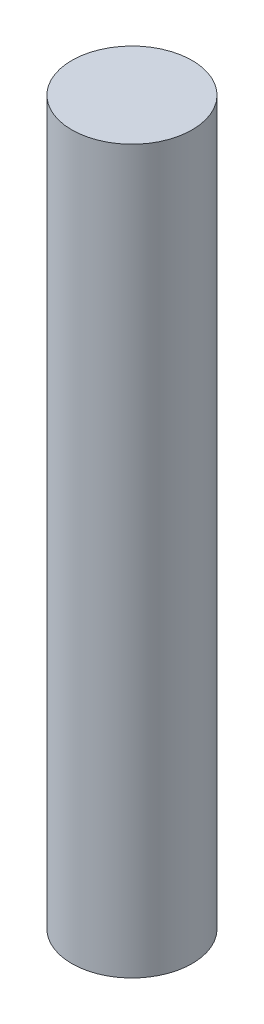
SolidWorks part; units mm, degrees
material "AISI 1020"
ref_plane "Front Plane" through (0, 0, 0) normal (0, 0, 1) x (1, 0, 0)
ref_plane "Top Plane" through (0, 0, 0) normal (0, 1, 0) x (1, 0, 0)
ref_plane "Right Plane" through (0, 0, 0) normal (1, 0, 0) x (0, 0, -1)
sketch "Sketch1" plane through (0, 0, 0) normal (0, 1, 0) x (1, 0, 0)
  circle A0 centre (0, 0) radius 1
  dimension "D1" = 2
extrude "Boss-Extrude1" add sketch "Sketch1" along normal blind 12
equation "\"D1@Sketch1\"=\"impeller dowel diameter\""
equation "\"D1@Boss-Extrude1\"=\"impeller dowel length\" "
equation "\"bearing OD\"= 30mm"
equation "\"bearing outer race thickness\"= 1mm"
equation "\"bearing ID\"= 10mm"
equation "\"bearing depth\"= 9mm"
equation "\"bearing inner race thickness\"= 1mm"
equation "\"small seal OD\"= 20mm"
equation "\"small seal ID\"= 8mm"
equation "\"small seal depth\"= 6mm"
equation "\"big seal OD\"= 30mm"
equation "\"big seal ID\"= 15mm"
equation "\"big seal depth\"= 8mm"
equation "\"z\"= 6"
equation "\"de\"= .4in"
equation "\"d2\"= 1.4in"
equation "\"d_exit\"=\"b2\""
equation "\"theta\"= 15"
equation "\"b2\"= .1117in"
equation "\"b1\"= \"b2\" + (\"d2\"/2 - \"de\"/2)*sin(\"theta\")"
equation "\"s\"= ( 1/\"z\")*(3.14*\"de\" - (3.14*(\"de\"^2) / (4*(\"b1\"))))"
equation "\"s_opening\"= (3.14*\"de\" - \"z\"*\"s\")/\"z\""
equation "\"area_eye\"=3.14*(\"de\"^2)/4"
equation "\"single_channel_area\"=\"s_opening\"*\"b1\""
equation "\"impeller upper clearance\"= .5mm"
equation "\"impeller horizontal clearance\"= .5mm"
equation "\"impeller bottom clearance\"= .5mm"
equation "\"impeller base thickness\"= 2mm"
equation "\"impeller boss depth\"= 14mm"
equation "\"impeller dowel diameter\"= 2mm"
equation "\"impeller bolt head diameter\"= 7.5mm"
equation "\"impeller bolt head depth\"= 4mm"
equation "\"impeller boss diameter\"= \"big seal ID\""
equation "\"impeller shaft bore\"= 8mm"
equation "\"impeller shaft bore depth\"= \"impeller boss depth\" + \"impeller base thickness\" - \"impeller bolt head depth\" - 3mm"
equation "\"impeller dowel length\"= 2mm*2 + \"impeller shaft bore\""
equation "\"impeller screw hole bore\"= 4mm"
equation "\"shaft impeller screw hole diameter\"= \"impeller screw hole bore\""
equation "\"shaft impeller section length\"= \"impeller shaft bore depth\""
equation "\"shaft impeller screw hole depth\"= \"shaft impeller section length\"-\"impeller dowel diameter\"-2mm"
equation "\"shaft impeller section diameter\"= \"impeller shaft bore\""
equation "\"shaft seal section diameter\"=\"small seal ID\""
equation "\"shaft seal section length\"=\"small seal depth\" + 2mm"
equation "\"shaft bearing section diameter\"= \"bearing ID\""
equation "\"shaft bearing section length\"= \"bearing depth\""
equation "\"shaft bearing stop diameter\"= \"bearing ID\" + 2mm"
equation "\"shaft bearing stop length\"= 2mm"
equation "\"shaft coupler section diameter\"= 8mm"
equation "\"shaft coupler section length\"= 20mm"
equation "\"coupler set screw drill hole ID\"= 6mm"
equation "\"coupler set screw 1 distance\"= \"motor mount shaft hole depth\" / 3"
equation "\"coupler set screw 2 distance\"= \"motor mount shaft hole depth\" * 4 / 5"
equation "\"coupler motor shaft hole ID\"= 8mm"
equation "\"coupler impeller shaft hole ID\"= \"shaft coupler section diameter\""
equation "\"coupler OD\"= 18mm"
equation "\"coupler length\"= \"motor mount shaft hole depth\" + 10mm"
equation "\"bearing plate bearing recess\"= \"bearing depth\""
equation "\"bearing plate bearing clearance\"= \"shaft bearing stop length\" + 2mm"
equation "\"seal plate small seal recess depth\"= \"small seal depth\""
equation "\"seal plate small seal recess OD\"= \"small seal OD\""
equation "\"seal plate lip depth\"= 2mm"
equation "\"seal plate lip ID\"= \"small seal OD\" - 3mm"
equation "\"seal plate thickness\"= \"seal plate small seal recess depth\" + \"seal plate lip depth\" + \"seal plate lip depth\""
equation "\"motor to housing distance\"= 60mm"
equation "\"motor mount pattern diameter\"= 30mm"
equation "\"motor mount to housing m8 screw hole diameter\"= 8.5mm"
equation "\"motor mount to housing m8 screw post radius\"= ( 3 * \"motor mount to housing m8 screw hole diameter\" ) / 2"
equation "\"motor mount to housing m8 pattern diameter\"= 100mm"
equation "\"motor mount to housing m4 screw hole diameter\"= 4mm"
equation "\"motor mount to housing m4 head diameter\"= 7.25mm"
equation "\"motor mount to housing m4 head depth\"= 4mm"
equation "\"motor mount plate thickness\"= 6mm + \"motor mount m4 head depth\""
equation "\"housing bearing seat lip thickness\"= 2mm"
equation "\"housing base thickness\"= \"housing bearing seat lip thickness\" + \"bearing depth\""
equation "\"impeller cavity center height\"= \"impeller bottom clearance\" + \"impeller base thickness\" + \"b1\" + \"impeller upper clearance\""
equation "\"impeller cavity diameter\"= 2 * \"impeller horizontal clearance\" + \"d2\""
equation "\"impeller cavity outer height\"= \"impeller bottom clearance\" + \"impeller upper clearance\" + \"impeller base thickness\" + \"b2\""
equation "\"housing top o-ring channel height\"= 1.5mm"
equation "\"housing top o ring channel width\"= 1.5mm"
equation "\"housing top o-ring diameter\"= 3in"
equation "\"housing top threaded inlet depth\"= 8mm"
equation "\"housing top total thickness\"= \"housing top threaded inlet depth\" + \"impeller cavity center height\""
equation "\"housing top total width\"= 10mm"
equation "\"housing top exit threaded diameter\"= 8mm"
equation "\"housing top exit threaded depth\"= 8mm"
equation "\"motor shaft pride\"= 32mm"
equation "\"motor shaft flat section length from tip\"= 25.7mm"
equation "\"motor shaft bore end clearance\"= 2mm"
equation "\"coupler shaft to motor clearance\"= 2mm"
equation "\"motor mount shaft hole depth\"= \"motor shaft pride\""
